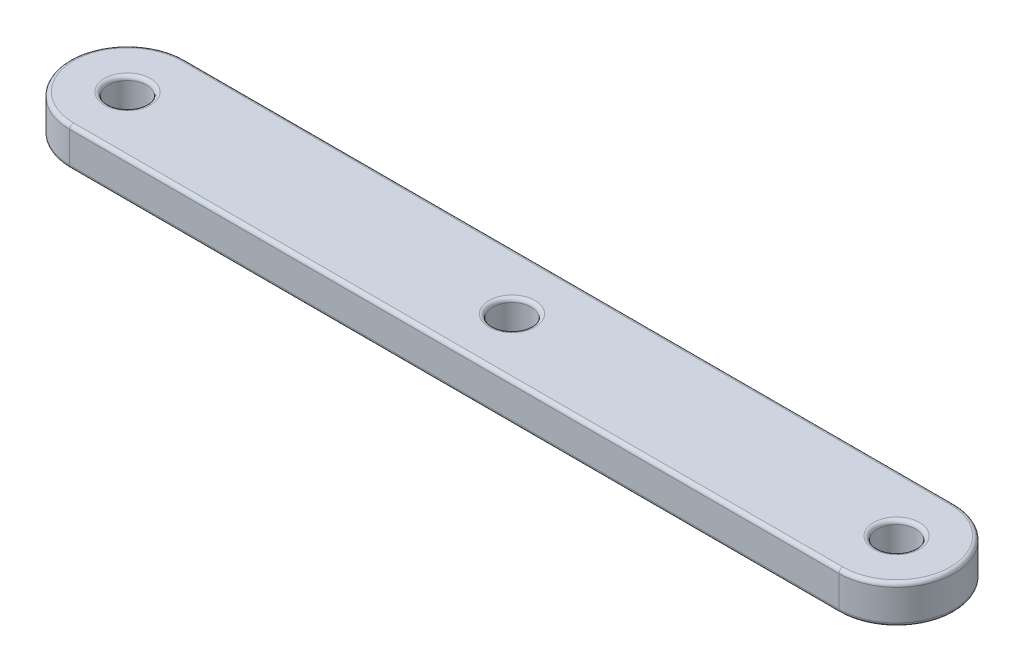
SolidWorks part; units mm, degrees
ref_plane "前视基准面" through (0, 0, 0) normal (0, 0, 1) x (1, 0, 0)
ref_plane "上视基准面" through (0, 0, 0) normal (0, 1, 0) x (1, 0, 0)
ref_plane "右视基准面" through (0, 0, 0) normal (1, 0, 0) x (0, 0, -1)
other "Configuration Table"
sketch "草图1" plane through (0, 0, 0) normal (0, 1, 0) x (1, 0, 0)
  line L0 (0, 0) -> (200, 0) construction
  line L1 (0, 15) -> (200, 15)
  line L2 (0, -15) -> (200, -15)
  arc A0 (0, 15) -> (0, -15) centre (0, 0) ccw
  arc A1 (200, -15) -> (200, 15) centre (200, 0) ccw
  circle A2 centre (200, 0) radius 5
  circle A3 centre (100, 0) radius 5
  circle A4 centre (0, 0) radius 5
  point P3 (100, 0)
  dimension "D2" = 15
  dimension "D3" = 10
  dimension "D4" = 10
  dimension "D5" = 10
  dimension "D1" = 200
extrude "凸台-拉伸1" add sketch "草图1" along normal blind 10
fillet "圆角1" radius 1 11 edges at (100, 10, -15) (215, 10, 0) (100, 10, 15) (-15, 10, 0) (0, 0, 5) (100, 0, 5) (200, 0, 5) (100, 0, 15) (215, 0, 0) (100, 0, -15) (-15, 0, 0)
fillet "圆角2" radius 1 3 edges at (0, 10, 5) (200, 10, 5) (100, 10, 5)
